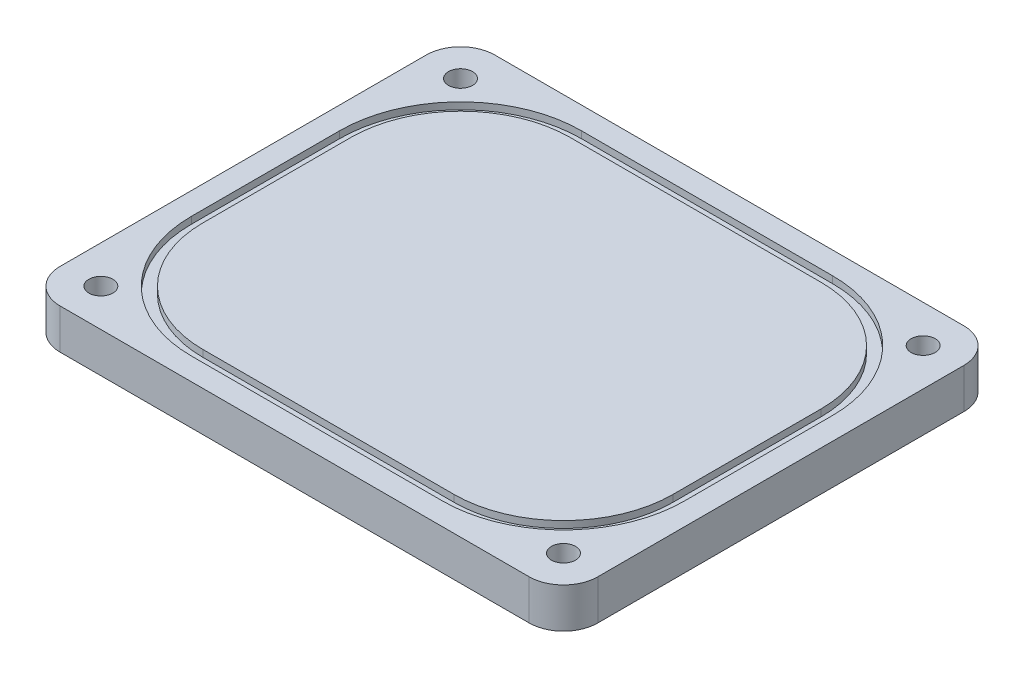
SolidWorks part; units mm, degrees
ref_plane "Front Plane" through (0, 0, 0) normal (0, 0, 1) x (1, 0, 0)
ref_plane "Top Plane" through (0, 0, 0) normal (0, 1, 0) x (1, 0, 0)
ref_plane "Right Plane" through (0, 0, 0) normal (1, 0, 0) x (0, 0, -1)
sketch "Sketch1" plane through (0, 0, 0) normal (0, 1, 0) x (1, 0, 0)
  line L1 (-47, -38) -> (47, -38)
  line L2 (-47, -38) -> (-47, 38)
  line L3 (-47, 38) -> (47, 38)
  line L4 (47, -38) -> (47, 38)
  line L5 (-47, -38) -> (47, 38) construction
  line L6 (-47, 38) -> (47, -38) construction
  point P0 (0, 0)
  dimension "D1" = 76
  dimension "D2" = 94
extrude "Boss-Extrude1" add sketch "Sketch1" along normal blind 7
fillet "Fillet1" radius 6 4 edges at (-47, 3.5, -38) (47, 3.5, -38) (47, 3.5, 38) (-47, 3.5, 38)
sketch "Sketch2" plane through (0, 7, 0) normal (0, 1, 0) x (1, 0, 0)
  line L0 (-47, 32) -> (-47, -32) construction
  line L1 (41, 38) -> (-41, 38) construction
  circle A0 centre (-40.44, 31.44) radius 2.1
  circle A1 centre (40.44, 31.44) radius 2.1
  circle A2 centre (40.44, -31.44) radius 2.1
  circle A3 centre (-40.44, -31.44) radius 2.1
  dimension "D2" = 4.2
  dimension "D1" = 6.56
  dimension "6.56" = 6.56
  dimension "D3" = 2
  dimension "D4" = 2
extrude "Cut-Extrude1" cut sketch "Sketch2" against normal through all both and the other way through all
sketch "Sketch3" plane through (0, 7, 0) normal (0, 1, 0) x (1, 0, 0)
  line L0 (-41.1, -12.96) -> (-41.1, 12.96)
  line L1 (-40.44, -31.44) -> (40.44, -31.44) construction
  line L2 (-40.44, -31.44) -> (-40.44, 31.44) construction
  line L3 (-40.44, 31.44) -> (40.44, 31.44) construction
  line L4 (40.44, -31.44) -> (40.44, 31.44) construction
  line L5 (-40.44, -31.44) -> (40.44, 31.44) construction
  line L6 (-40.44, 31.44) -> (40.44, -31.44) construction
  line L7 (21.96, 32.1) -> (-21.96, 32.1)
  line L8 (0, 32.1) -> (0, -31.44) construction
  line L9 (-41.1, 0) -> (40.44, 0) construction
  line L10 (-21.96, 34.1) -> (21.96, 34.1)
  line L11 (-43.1, -12.96) -> (-43.1, 12.96)
  line L12 (-21.96, -34.1) -> (21.96, -34.1)
  line L13 (21.96, -32.1) -> (-21.96, -32.1)
  line L14 (41.1, -12.96) -> (41.1, 12.96)
  line L15 (43.1, -12.96) -> (43.1, 12.96)
  arc A0 (-41.1, 12.96) -> (-21.96, 32.1) centre (-21.96, 12.96) cw
  arc A1 (-43.1, 12.96) -> (-21.96, 34.1) centre (-21.96, 12.96) cw
  arc A2 (-41.1, -12.96) -> (-21.96, -32.1) centre (-21.96, -12.96) ccw
  arc A3 (-43.1, -12.96) -> (-21.96, -34.1) centre (-21.96, -12.96) ccw
  arc A4 (43.1, 12.96) -> (21.96, 34.1) centre (21.96, 12.96) ccw
  arc A5 (41.1, 12.96) -> (21.96, 32.1) centre (21.96, 12.96) ccw
  arc A6 (41.1, -12.96) -> (21.96, -32.1) centre (21.96, -12.96) cw
  arc A7 (43.1, -12.96) -> (21.96, -34.1) centre (21.96, -12.96) cw
  point P0 (0, 0)
  point P10 (-41.1, 0)
  point P13 (0, 32.1)
  dimension "D1" = 41.1
  dimension "D2" = 25.92
  dimension "D3" = 32.1
  dimension "D4" = 43.92
  dimension "D5" = 2
extrude "Cut-Extrude2" cut sketch "Sketch3" against normal blind 1.2
sketch "Sketch4" plane through (0, 0, 0) normal (0, -1, 0) x (1, 0, 0)
  line L1 (-44.1828, 34.9606) -> (-45.3604, 29.959)
  line L2 (-45.3604, 29.959) -> (-41.6176, 26.4383)
  line L3 (-41.6176, 26.4383) -> (-36.6972, 27.9194)
  line L4 (-36.6972, 27.9194) -> (-35.5196, 32.921)
  line L5 (-35.5196, 32.921) -> (-39.2624, 36.4417)
  line L6 (-39.2624, 36.4417) -> (-44.1828, 34.9606)
  line L7 (44.0901, 35.0567) -> (39.1329, 36.4094)
  line L8 (39.1329, 36.4094) -> (35.4828, 32.7927)
  line L9 (35.4828, 32.7927) -> (36.7899, 27.8233)
  line L10 (36.7899, 27.8233) -> (41.7471, 26.4706)
  line L11 (41.7471, 26.4706) -> (45.3972, 30.0873)
  line L12 (45.3972, 30.0873) -> (44.0901, 35.0567)
  line L13 (44.0581, -35.0886) -> (45.4089, -30.1309)
  line L14 (45.4089, -30.1309) -> (41.7908, -26.4823)
  line L15 (41.7908, -26.4823) -> (36.8219, -27.7914)
  line L16 (36.8219, -27.7914) -> (35.4711, -32.7491)
  line L17 (35.4711, -32.7491) -> (39.0892, -36.3977)
  line L18 (39.0892, -36.3977) -> (44.0581, -35.0886)
  line L19 (-44.0106, -35.1352) -> (-39.0252, -36.3798)
  line L20 (-39.0252, -36.3798) -> (-35.4546, -32.6846)
  line L21 (-35.4546, -32.6846) -> (-36.8694, -27.7448)
  line L22 (-36.8694, -27.7448) -> (-41.8548, -26.5002)
  line L23 (-41.8548, -26.5002) -> (-45.4254, -30.1954)
  line L24 (-45.4254, -30.1954) -> (-44.0106, -35.1352)
  circle A5 centre (-40.44, 31.44) radius 4.45 construction
  circle A6 centre (40.44, 31.44) radius 4.45 construction
  circle A7 centre (40.44, -31.44) radius 4.45 construction
  circle A8 centre (-40.44, -31.44) radius 4.45 construction
  dimension "D1" = 8.9
  dimension "D2" = 8.9
  dimension "D3" = 8.9
  dimension "D4" = 8.9
extrude "Cut-Extrude5" cut sketch "Sketch4" against normal blind 3.5
sketch "Sketch6" plane through (0, 0, 0) normal (0, -1, 0) x (1, 0, 0)
  line L0 (-27.5964, 0) -> (27.5964, 0) construction
  text T0 "V3"
  point P4 (0, 0)
extrude "Cut-Extrude6" cut sketch "Sketch6" against normal blind 0.25
